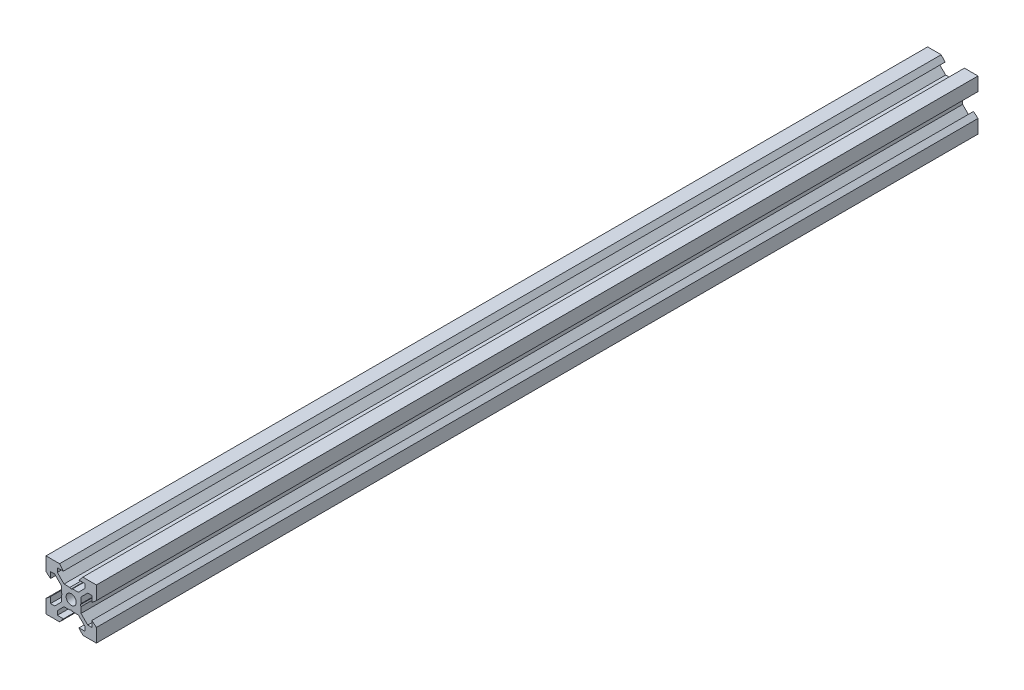
SolidWorks part; units mm, degrees
material "6063-O"
ref_plane "Front Plane" through (0, 0, 0) normal (0, 0, 1) x (1, 0, 0)
ref_plane "Top Plane" through (0, 0, 0) normal (0, 1, 0) x (1, 0, 0)
ref_plane "Right Plane" through (0, 0, 0) normal (1, 0, 0) x (0, 0, -1)
sketch "Sketch1" plane through (0, 0, 0) normal (0, 0, 1) x (1, 0, 0)
  line L0 (10, 10) -> (4.6104, 10) construction
  line L1 (10, 10) -> (10, 4.6104) construction
  line L2 (10, -10) -> (10, -4.6104) construction
  line L3 (10, -10) -> (4.6104, -10) construction
  line L4 (10, 10) -> (10, 4.6104)
  line L5 (6.5607, 5.5) -> (8.2, 5.5)
  line L6 (5.5, 8.2) -> (5.5, 6.5607)
  line L7 (10, 10) -> (4.6104, 10)
  line L8 (10, 10) -> (10, 4.6104)
  line L9 (6.5607, 5.5) -> (3.9, 2.8393)
  line L10 (5.5, 6.5607) -> (2.8393, 3.9)
  line L11 (10, 4.6104) -> (8.2, 3.1)
  line L12 (4.6104, 10) -> (3.1, 8.2)
  line L13 (8.2, 3.1) -> (8.2, 5.5)
  line L14 (3.1, 8.2) -> (5.5, 8.2)
  line L15 (-6.5607, 5.5) -> (-8.2, 5.5)
  line L16 (6.5607, -5.5) -> (8.2, -5.5)
  line L17 (3.1, -8.2) -> (5.5, -8.2)
  line L18 (8.2, -3.1) -> (8.2, -5.5)
  line L19 (4.6104, -10) -> (3.1, -8.2)
  line L20 (10, -4.6104) -> (8.2, -3.1)
  line L21 (0.5196, -3.9) -> (0, -3.6)
  line L22 (0.5196, 3.9) -> (0, 3.6)
  line L23 (3.6, 0) -> (3.9, -0.5196)
  line L24 (3.9, 0.5196) -> (3.6, 0)
  line L25 (3.9, 0.5196) -> (3.9, 2.8393)
  line L26 (2.8393, 3.9) -> (0.5196, 3.9)
  line L27 (3.9, -2.8393) -> (3.9, -0.5196)
  line L28 (2.8393, -3.9) -> (0.5196, -3.9)
  line L29 (5.5, -6.5607) -> (2.8393, -3.9)
  line L30 (6.5607, -5.5) -> (3.9, -2.8393)
  line L31 (10, -10) -> (10, -4.6104)
  line L32 (10, -10) -> (4.6104, -10)
  line L33 (5.5, -8.2) -> (5.5, -6.5607)
  line L34 (-6.5607, -5.5) -> (-8.2, -5.5)
  line L35 (10, -10) -> (10, -4.6104)
  line L36 (0, 0) -> (0, 8.2) construction
  line L37 (-10, -10) -> (-4.6104, -10) construction
  line L38 (-10, -10) -> (-10, -4.6104) construction
  line L39 (-10, 10) -> (-10, 4.6104) construction
  line L40 (-10, 10) -> (-4.6104, 10) construction
  line L41 (-10, -10) -> (-10, -4.6104)
  line L43 (-5.5, -8.2) -> (-5.5, -6.5607)
  line L44 (-10, -10) -> (-4.6104, -10)
  line L45 (-10, -10) -> (-10, -4.6104)
  line L46 (-6.5607, -5.5) -> (-3.9, -2.8393)
  line L47 (-5.5, -6.5607) -> (-2.8393, -3.9)
  line L48 (-2.8393, -3.9) -> (-0.5196, -3.9)
  line L49 (-3.9, -2.8393) -> (-3.9, -0.5196)
  line L50 (-2.8393, 3.9) -> (-0.5196, 3.9)
  line L51 (-3.9, 0.5196) -> (-3.9, 2.8393)
  line L52 (-3.9, 0.5196) -> (-3.6, 0)
  line L53 (-3.6, 0) -> (-3.9, -0.5196)
  line L54 (-0.5196, 3.9) -> (0, 3.6)
  line L55 (-0.5196, -3.9) -> (0, -3.6)
  line L56 (-10, -4.6104) -> (-8.2, -3.1)
  line L57 (-4.6104, -10) -> (-3.1, -8.2)
  line L58 (-8.2, -3.1) -> (-8.2, -5.5)
  line L59 (-3.1, -8.2) -> (-5.5, -8.2)
  line L60 (-10, -10) -> (10, -10) construction
  line L61 (-10, -10) -> (-10, 10) construction
  line L62 (-3.1, 8.2) -> (-5.5, 8.2)
  line L63 (-8.2, 3.1) -> (-8.2, 5.5)
  line L64 (-4.6104, 10) -> (-3.1, 8.2)
  line L65 (-10, 4.6104) -> (-8.2, 3.1)
  line L66 (-5.5, 6.5607) -> (-2.8393, 3.9)
  line L67 (-6.5607, 5.5) -> (-3.9, 2.8393)
  line L68 (-10, 10) -> (-10, 4.6104)
  line L69 (-10, 10) -> (-4.6104, 10)
  line L70 (-5.5, 8.2) -> (-5.5, 6.5607)
  line L71 (-10, 10) -> (10, 10) construction
  line L72 (-10, 10) -> (-10, 4.6104)
  line L73 (10, -10) -> (10, 10) construction
  line L74 (-10, -10) -> (10, 10) construction
  line L75 (-10, 10) -> (10, -10) construction
  circle A0 centre (0, 0) radius 2
  dimension "D7" = 4
  dimension "D1" = 20
  dimension "D2" = 5.3896
  dimension "D3" = 4.5
  dimension "D4" = 50
  dimension "D5" = 1.8
  dimension "D6" = 1.5104
  dimension "D8" = 5.5
  dimension "D9" = 120
  dimension "D10" = 0.3
  dimension "D11" = 2.3197
  dimension "D12" = 7.8
  dimension "D13" = 7.8
  dimension "D14" = 1.5
  dimension "D15" = 2.6607
extrude "Boss-Extrude1" add sketch "Sketch1" along normal mid plane 350 contours L70 L62 L64 L69 L68 L65 L63 L15 L67 L51 L52 L53 L49 L46 L34 L58 L56 L41 L44 L57 L59 L43 L47 L48 L55 L21 L28 L29 L33 L17 L19 L32 L31 L20 L18 L16 L30 L27 L23 L24 L25 L9 L5 L13 L11 L4 L7 L12 L14 L6 L10
